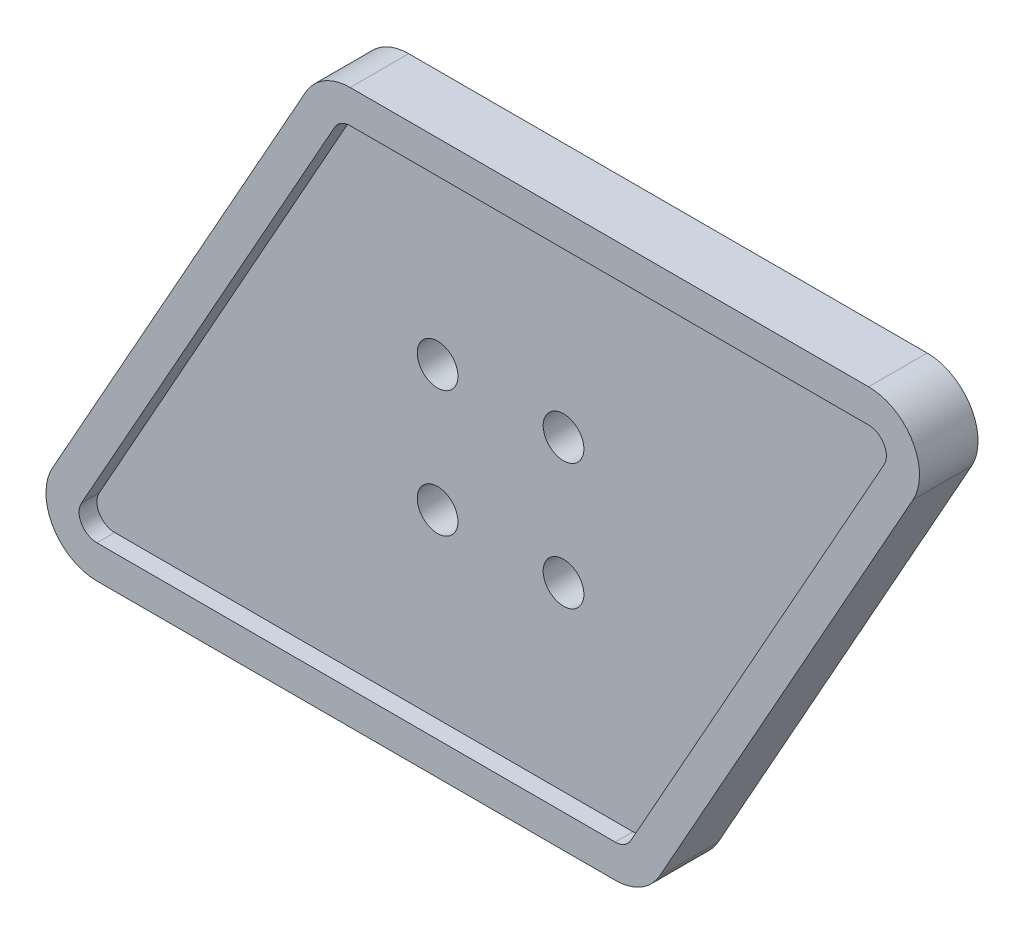
SolidWorks part; units mm, degrees
ref_plane "Front Plane" through (0, 0, 0) normal (0, 0, 1) x (1, 0, 0)
ref_plane "Top Plane" through (0, 0, 0) normal (0, 1, 0) x (1, 0, 0)
ref_plane "Right Plane" through (0, 0, 0) normal (1, 0, 0) x (0, 0, -1)
sketch "Sketch1" plane through (0, 0, 0) normal (0, 0, 1) x (1, 0, 0)
  line L1 (-4.9497, 4.9497) -> (4.9497, 4.9497) construction
  line L2 (-4.9497, 4.9497) -> (-4.9497, -4.9497) construction
  line L3 (-4.9497, -4.9497) -> (4.9497, -4.9497) construction
  line L4 (4.9497, 4.9497) -> (4.9497, -4.9497) construction
  line L5 (-4.9497, 4.9497) -> (4.9497, -4.9497) construction
  line L6 (-4.9497, -4.9497) -> (4.9497, 4.9497) construction
  line L14 (-33.8156, -15.818) -> (-13.9057, 19.7275)
  line L15 (-10.4159, 21.7727) -> (30.3258, 21.7727)
  line L16 (33.8156, 15.818) -> (13.9057, -19.7275)
  line L17 (10.4159, -21.7727) -> (-30.3258, -21.7727)
  line L18 (-12.7601, 21.7727) -> (12.7601, -21.7727) construction
  line L19 (-37.151, -21.7727) -> (37.151, 21.7727) construction
  circle A1 centre (-4.9497, 4.9497) radius 1.6
  circle A2 centre (4.9497, 4.9497) radius 1.6
  circle A3 centre (4.9497, -4.9497) radius 1.6
  circle A4 centre (-4.9497, -4.9497) radius 1.6
  arc A5 (13.9057, -19.7275) -> (10.4159, -21.7727) centre (10.4159, -17.7727) cw
  arc A6 (-33.8156, -15.818) -> (-30.3258, -21.7727) centre (-30.3258, -17.7727) ccw
  arc A7 (30.3258, 21.7727) -> (33.8156, 15.818) centre (30.3258, 17.7727) cw
  arc A8 (-13.9057, 19.7275) -> (-10.4159, 21.7727) centre (-10.4159, 17.7727) cw
  point P2 (0, 0)
  point P11 (0, 0)
  point P14 (0, 0)
  point P15 (-4.9497, 22)
  point P16 (-0.7737, 20.7751)
  point P17 (0, 24.6978)
  point P18 (-10.6264, 24.8637)
  point P19 (43.5067, 18.0326)
  point P20 (43.0176, 21.75)
  point P21 (0, 0)
  point P22 (-51.8728, -21.75)
  point P35 (-33.7768, -19.7952)
  point P36 (33.7768, 19.7952)
  point P37 (-12.4384, 21.2237)
  point P39 (12.4384, -21.2237)
  point P40 (0, 0)
  point P41 (0, 0)
  dimension "D1" = 4
  dimension "D3" = 3.2
  dimension "D4" = 78.3
  dimension "D5" = 49.2
  dimension "D2" = 14
extrude "Boss-Extrude1" add sketch "Sketch1" along normal blind 4.6
sketch "Sketch5" plane through (0, 0, 4.6) normal (0, 0, 1) x (1, 0, 0)
  line L8 (11.6373, -18.4569) -> (31.5472, 17.0886)
  line L9 (30.3258, 19.1727) -> (-10.4159, 19.1727)
  line L10 (-11.6373, 18.4569) -> (-31.5472, -17.0886)
  line L11 (-30.3258, -19.1727) -> (10.4159, -19.1727)
  line L12 (11.6373, -18.4569) -> (31.5472, 17.0886)
  line L13 (30.3258, 19.1727) -> (-10.4159, 19.1727)
  line L14 (-11.6373, 18.4569) -> (-31.5472, -17.0886)
  line L15 (-30.3258, -19.1727) -> (10.4159, -19.1727)
  arc A8 (10.4159, -19.1727) -> (11.6373, -18.4569) centre (10.4159, -17.7727) ccw
  arc A9 (31.5472, 17.0886) -> (30.3258, 19.1727) centre (30.3258, 17.7727) ccw
  arc A10 (-10.4159, 19.1727) -> (-11.6373, 18.4569) centre (-10.4159, 17.7727) ccw
  arc A11 (-31.5472, -17.0886) -> (-30.3258, -19.1727) centre (-30.3258, -17.7727) ccw
  arc A12 (10.4159, -19.1727) -> (11.6373, -18.4569) centre (10.4159, -17.7727) ccw
  arc A13 (31.5472, 17.0886) -> (30.3258, 19.1727) centre (30.3258, 17.7727) ccw
  arc A14 (-10.4159, 19.1727) -> (-11.6373, 18.4569) centre (-10.4159, 17.7727) ccw
  arc A15 (-31.5472, -17.0886) -> (-30.3258, -19.1727) centre (-30.3258, -17.7727) ccw
  dimension "D1" = 2.6
extrude "Cut-Extrude4" cut sketch "Sketch5" against normal blind 1.4
